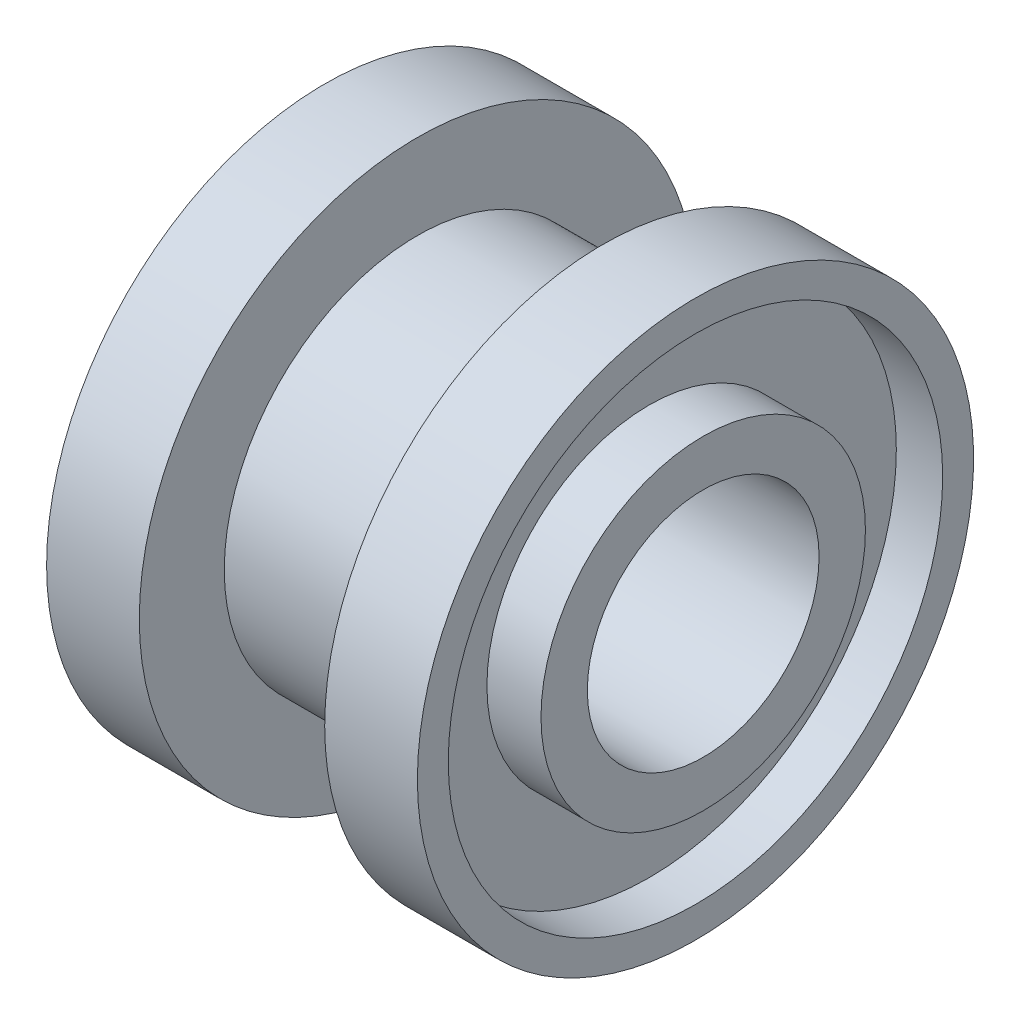
SolidWorks part; units mm, degrees
material "PS HI"
ref_plane "Płaszczyzna przednia" through (0, 0, 0) normal (0, 0, 1) x (1, 0, 0)
ref_plane "Płaszczyzna górna" through (0, 0, 0) normal (0, 1, 0) x (1, 0, 0)
ref_plane "Płaszczyzna prawa" through (0, 0, 0) normal (1, 0, 0) x (0, 0, -1)
sketch "Szkic1" plane through (0, 0, 0) normal (0, 0, 1) x (1, 0, 0)
  line L0 (-30.8375, 0) -> (30.8375, 0) construction
  line L1 (0, -37.8176) -> (0, 37.8176) construction
  line L2 (-6, 12.5) -> (6, 12.5)
  line L3 (6, 12.5) -> (6, 18)
  line L4 (6, 18) -> (12, 18)
  line L5 (12, 18) -> (12, 16)
  line L6 (12, 16) -> (9, 16)
  line L7 (9, 16) -> (9, 10.5)
  line L10 (-12, 16) -> (-9, 16)
  line L11 (-12, 18) -> (-12, 16)
  line L12 (-6, 18) -> (-12, 18)
  line L13 (-6, 12.5) -> (-6, 18)
  line L15 (12.5, 7.5) -> (12.5, 10.5)
  line L16 (12.5, 10.5) -> (9, 10.5)
  line L18 (-9, 16) -> (-9, 10.5)
  line L20 (-12.5, 7.5) -> (-12.5, 10.5)
  line L21 (-12.5, 10.5) -> (-9, 10.5)
  line L22 (12.5, 7.5) -> (-12.5, 7.5)
  point P1 (12, 17)
  point P7 (0, 0)
  point P14 (0, 7.5)
  point P21 (0, 12.5)
  point P23 (12.5, 9)
  dimension "D1" = 15
  dimension "D2" = 25
  dimension "D3" = 32
  dimension "D4" = 36
  dimension "D5" = 3
  dimension "D6" = 6
  dimension "D7" = 12
  dimension "D8" = 21
  dimension "D9" = 3.5
  dimension "D10" = 25
revolve "Obrót1" add sketch "Szkic1" angle 360 about L0
sketch "Szkic2" plane through (-12, 0, 0) normal (-1, 0, 0) x (0, 0, 1)
  line L0 (0, 18) -> (0, 16) construction
  circle A0 centre (0, 17) radius 0.5
  dimension "D1" = 1
extrude "Wytnij-wyciągnięcie1" cut sketch "Szkic2" against normal blind 1
